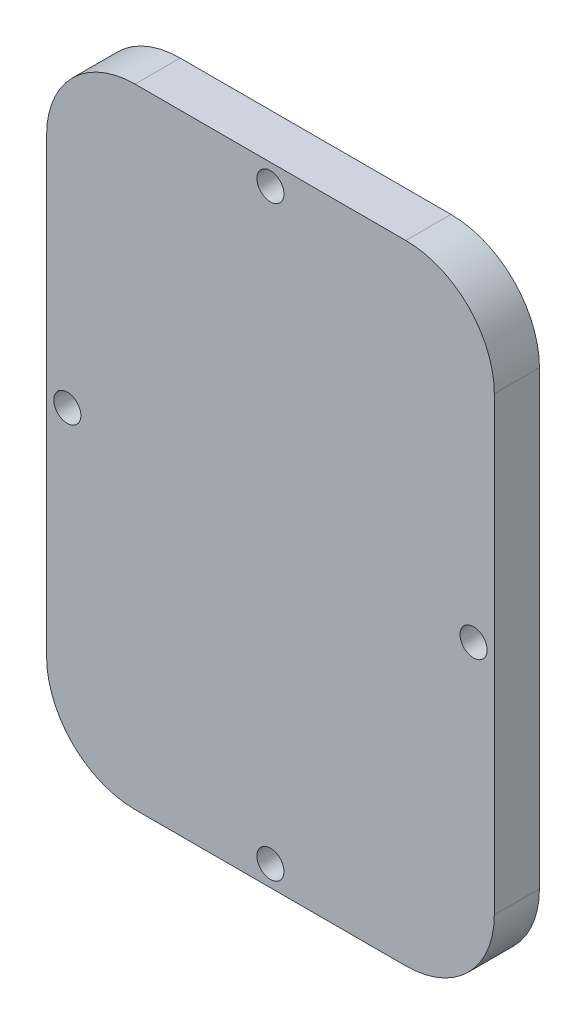
SolidWorks part; units mm, degrees
ref_plane "Plano frontal" through (0, 0, 0) normal (0, 0, 1) x (1, 0, 0)
ref_plane "Plano superior" through (0, 0, 0) normal (0, 1, 0) x (1, 0, 0)
ref_plane "Plano direito" through (0, 0, 0) normal (1, 0, 0) x (0, 0, -1)
sketch "Esboço1" plane through (0, 0, 0) normal (0, 0, 1) x (1, 0, 0)
  line L0 (15, 34.8) -> (-15, 34.8)
  line L1 (15, -35) -> (-15, -35)
  line L2 (25, -25) -> (25, 25)
  line L3 (15, 35) -> (-15, 35)
  line L4 (-25, -25) -> (-25, 25)
  line L5 (25, -35) -> (-25, 35) construction
  line L6 (25, 35) -> (-25, -35) construction
  line L7 (-24.8, -25) -> (-24.8, 25)
  line L8 (15, -34.8) -> (-15, -34.8)
  line L9 (24.8, -25) -> (24.8, 25)
  line L10 (0, 0) -> (0, 32.5) construction
  line L11 (0, 0) -> (22.5, 0) construction
  arc A0 (-15, -35) -> (-25, -25) centre (-15, -25) cw
  arc A1 (15, -35) -> (25, -25) centre (15, -25) ccw
  arc A2 (25, 25) -> (15, 35) centre (15, 25) ccw
  arc A3 (-15, 35) -> (-25, 25) centre (-15, 25) ccw
  arc A4 (-15, 34.8) -> (-24.8, 25) centre (-15, 25) ccw
  arc A5 (-15, -34.8) -> (-24.8, -25) centre (-15, -25) cw
  arc A6 (15, -34.8) -> (24.8, -25) centre (15, -25) ccw
  arc A7 (24.8, 25) -> (15, 34.8) centre (15, 25) ccw
  circle A8 centre (0, 32.5) radius 1.5
  circle A9 centre (22.5, 0) radius 1.5
  circle A10 centre (0, -32.5) radius 1.5
  circle A11 centre (-22.5, 0) radius 1.5
  point P0 (0, 0)
  dimension "D3" = 10
  dimension "D7" = 3
  dimension "D8" = 3
  dimension "D1" = 50
  dimension "D2" = 70
  dimension "D5" = 32.5
  dimension "D6" = 22.5
  dimension "D4" = 0.2
extrude "Ressalto-extrusão1" add sketch "Esboço1" along normal blind 5 contours L9 A7 L0 A4 L7 A5 L8 A6 A10 A9 A8 A11
